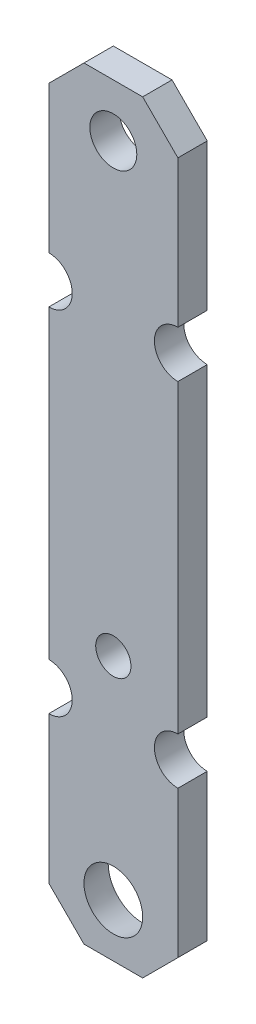
SolidWorks part; units mm, degrees
material "Acier allié"
ref_plane "Plan de face" through (0, 0, 0) normal (0, 0, 1) x (1, 0, 0)
ref_plane "Plan de dessus" through (0, 0, 0) normal (0, 1, 0) x (1, 0, 0)
ref_plane "Plan de droite" through (0, 0, 0) normal (1, 0, 0) x (0, 0, -1)
sketch "Esquisse1" plane through (0, 0, 0) normal (0, 0, 1) x (1, 0, 0)
  line L0 (0, 0) -> (0, 66.8196) construction
  line L1 (-5, 65) -> (5, 65)
  line L2 (5, 65) -> (11, 59)
  line L3 (-5, 65) -> (-11, 59)
  line L4 (11, 59) -> (11, 34)
  line L5 (-11, 59) -> (-11, 34)
  line L6 (11, 26) -> (11, -26)
  line L7 (-11, 26) -> (-11, -26)
  line L8 (-39.6125, 0) -> (36.5111, 0) construction
  line L9 (39.6125, 0) -> (-36.5111, 0) construction
  line L10 (-11, -59) -> (-11, -34)
  line L11 (11, -59) -> (11, -34)
  line L12 (-5, -65) -> (-11, -59)
  line L13 (5, -65) -> (11, -59)
  line L14 (-5, -65) -> (5, -65)
  arc A0 (11, 34) -> (11, 26) centre (11, 30) ccw
  arc A1 (-11, 34) -> (-11, 26) centre (-11, 30) cw
  arc A2 (-11, -34) -> (-11, -26) centre (-11, -30) ccw
  arc A3 (11, -34) -> (11, -26) centre (11, -30) cw
  circle A4 centre (0, 56) radius 4
  circle A5 centre (0, -20) radius 3
  point P6 (0, 65)
  point P9 (11, 0)
  point P26 (-11, 0)
  point P30 (0, -65)
  dimension "D3" = 4
  dimension "D7" = 8
  dimension "D9" = 6
  dimension "D1" = 65
  dimension "D2" = 35
  dimension "D4" = 45
  dimension "D5" = 6
  dimension "D6" = 22
  dimension "D8" = 56
  dimension "D10" = 45
extrude "Extrusion1" add sketch "Esquisse1" along normal blind 5
sketch "Esquisse2" plane through (0, 0, 0) normal (1, 0, 0) x (0, 0, -1)
  line L0 (5.7582, -56) -> (-11.019, -56) construction
  line L1 (-5, 56) -> (0, 56) construction
  line L2 (-5, -51) -> (0, -50.1184)
  line L3 (-5, -34) -> (-5, -59) construction
  line L4 (0, -34) -> (0, -59) construction
  line L5 (0, -52.0655) -> (0, -56)
  line L6 (0, -56) -> (-5, -56)
  line L7 (-5, -56) -> (-5, -51)
  line L8 (0, -52.0655) -> (0, -50.1184)
  dimension "D1" = 112
  dimension "D2" = 10
  dimension "D3" = 5
revolve "Enlèvement de matière-Révolution1" cut sketch "Esquisse2" angle 360 about L0
